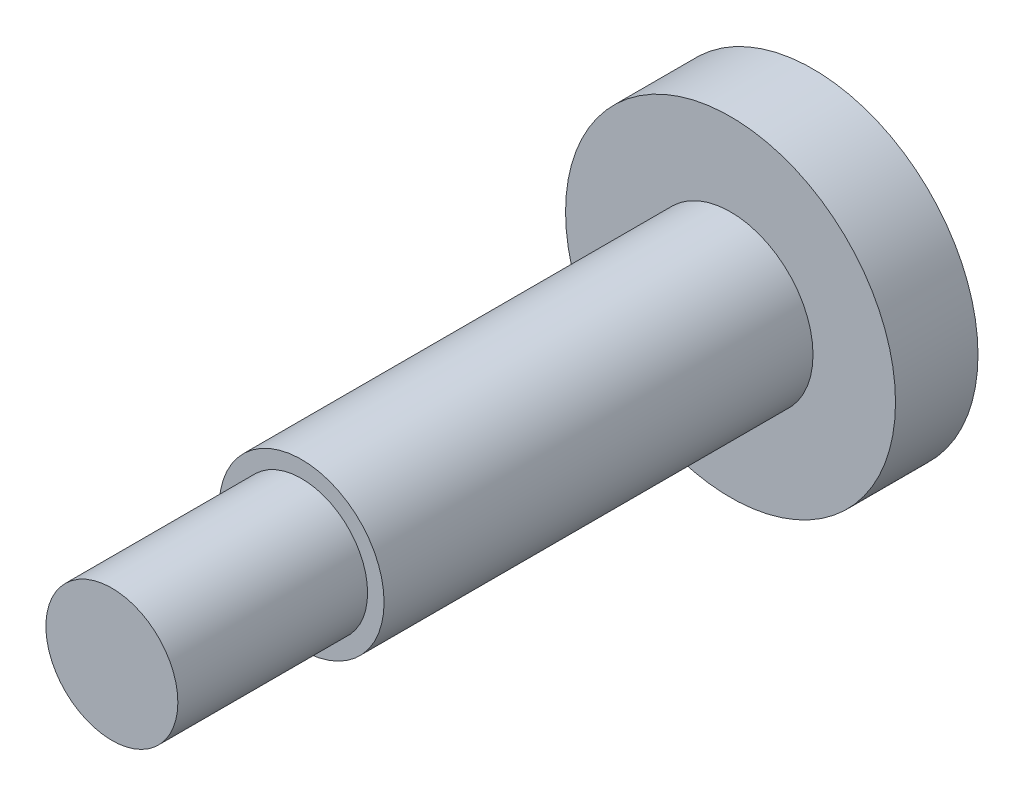
SolidWorks part; units mm, degrees
ref_plane "Front Plane" through (0, 0, 0) normal (0, 0, 1) x (1, 0, 0)
ref_plane "Top Plane" through (0, 0, 0) normal (0, 1, 0) x (1, 0, 0)
ref_plane "Right Plane" through (0, 0, 0) normal (1, 0, 0) x (0, 0, -1)
sketch "Sketch1" plane through (0, 0, 0) normal (0, 0, 1) x (1, 0, 0)
  circle A0 centre (0, 0) radius 2
extrude "Reference_Head" add sketch "Sketch1" along normal blind 1 from offset 1
sketch "Sketch2" plane through (0, 0, 0) normal (0, 0, 1) x (1, 0, 0)
  circle A0 centre (0, 0) radius 1
extrude "Reference_Shank" add sketch "Sketch2" along normal blind 7.5
sketch "Sketch3" plane through (0, 0, 7.5) normal (0, 0, 1) x (1, 0, 0)
  circle A0 centre (0, 0) radius 1.01
  circle A1 centre (0, 0) radius 0.8
extrude "M1p6_End_Thread_Envelope" cut sketch "Sketch3" against normal blind 2.3
